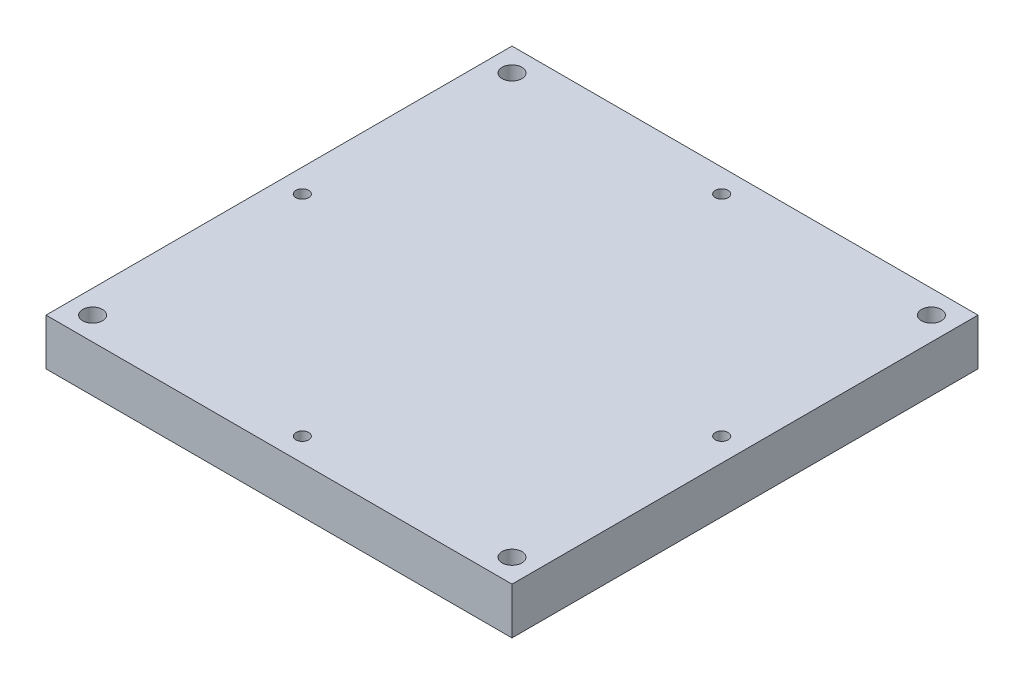
SolidWorks part; units mm, degrees
ref_plane "Front Plane" through (0, 0, 0) normal (0, 0, 1) x (1, 0, 0)
ref_plane "Top Plane" through (0, 0, 0) normal (0, 1, 0) x (1, 0, 0)
ref_plane "Right Plane" through (0, 0, 0) normal (1, 0, 0) x (0, 0, -1)
sketch "TowerBase" plane through (0, 0, 0) normal (0, 1, 0) x (1, 0, 0)
  line L1 (0, 0) -> (200, 0)
  line L2 (0, 0) -> (0, 200)
  line L3 (0, 200) -> (200, 200)
  line L4 (200, 0) -> (200, 200)
  dimension "D1" = 200
  dimension "D2" = 200
extrude "TowerBasePlate" add sketch "TowerBase" along normal blind 20
sketch "ScrewHoles" plane through (0, 20, 0) normal (0, 1, 0) x (1, 0, 0)
  line L0 (0, 0) -> (200, 0) construction
  line L1 (200, 200) -> (0, 200) construction
  line L2 (10, 100) -> (100, 100) construction
  line L3 (0, 200) -> (0, 0) construction
  circle A0 centre (10, 10) radius 4.25
  circle A1 centre (190, 10) radius 4.25
  circle A2 centre (190, 190) radius 4.25
  circle A3 centre (10, 190) radius 4.25
  circle A5 centre (10, 100) radius 2.75
  circle A6 centre (100, 100) radius 2.75 [skipped]
  circle A7 centre (190, 100) radius 2.75
  circle A8 centre (100, 190) radius 2.75
  circle A9 centre (190, 190) radius 2.75 [skipped]
  circle A10 centre (10, 190) radius 2.75 [skipped]
  circle A11 centre (100, 10) radius 2.75
  dimension "D2" = 8.5
  dimension "D9" = 5.5
  dimension "D16" = 5.5
  dimension "D1" = 10
  dimension "D3" = 10
  dimension "D6" = 10
  dimension "D7" = 180
  dimension "D8" = 10
  dimension "D10" = 90
  dimension "D11" = 90
  dimension "D14" = 180
  dimension "D15" = 90
  dimension "D17" = 90
  dimension "D18" = 90
  dimension "D19" = 90
  dimension "D4" = 2
  dimension "D5" = 2
  dimension "D12" = 3
  dimension "D13" = 2
extrude "Holes" cut sketch "ScrewHoles" against normal through all
